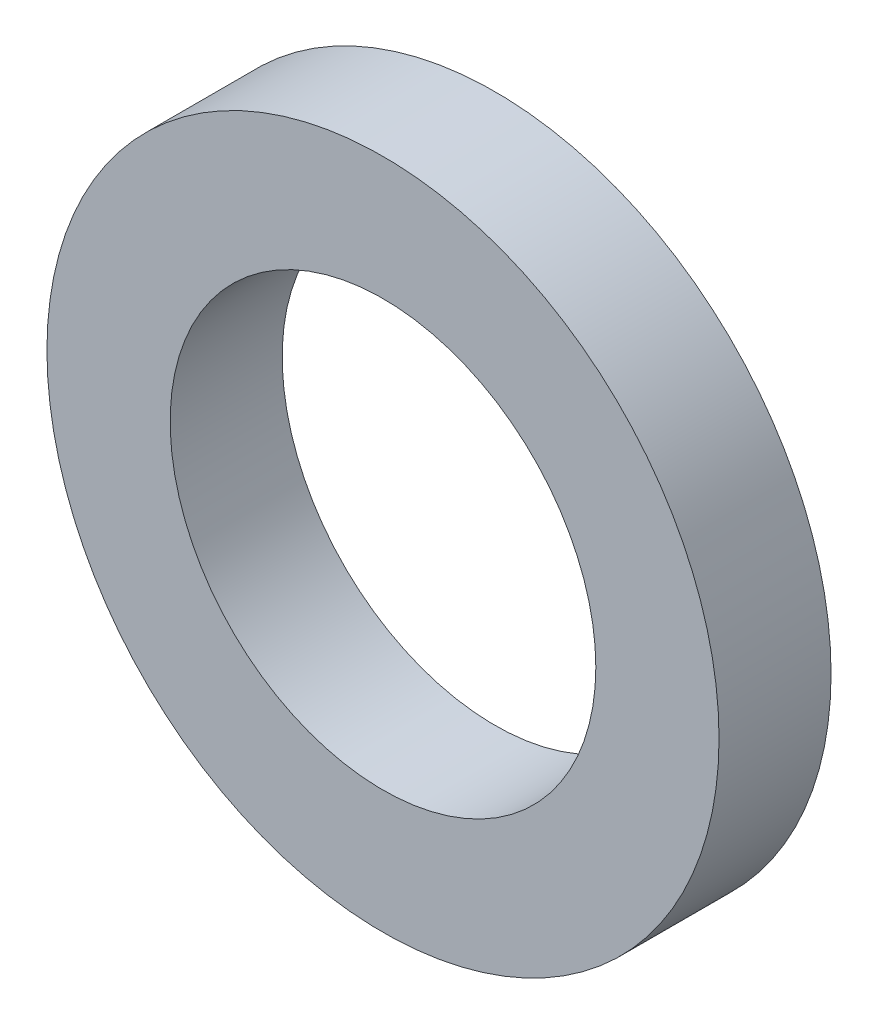
SolidWorks part; units mm, degrees
ref_plane "Front Plane" through (0, 0, 0) normal (0, 0, 1) x (1, 0, 0)
ref_plane "Top Plane" through (0, 0, 0) normal (0, 1, 0) x (1, 0, 0)
ref_plane "Right Plane" through (0, 0, 0) normal (1, 0, 0) x (0, 0, -1)
sketch "Sketch1" plane through (0, 0, 0) normal (0, 0, 1) x (1, 0, 0)
  circle A0 centre (0, 0) radius 3
  circle A1 centre (0, 0) radius 1.9
  dimension "D1" = 3.8
  dimension "D2" = 6
extrude "Boss-Extrude1" add sketch "Sketch1" along normal blind 1
